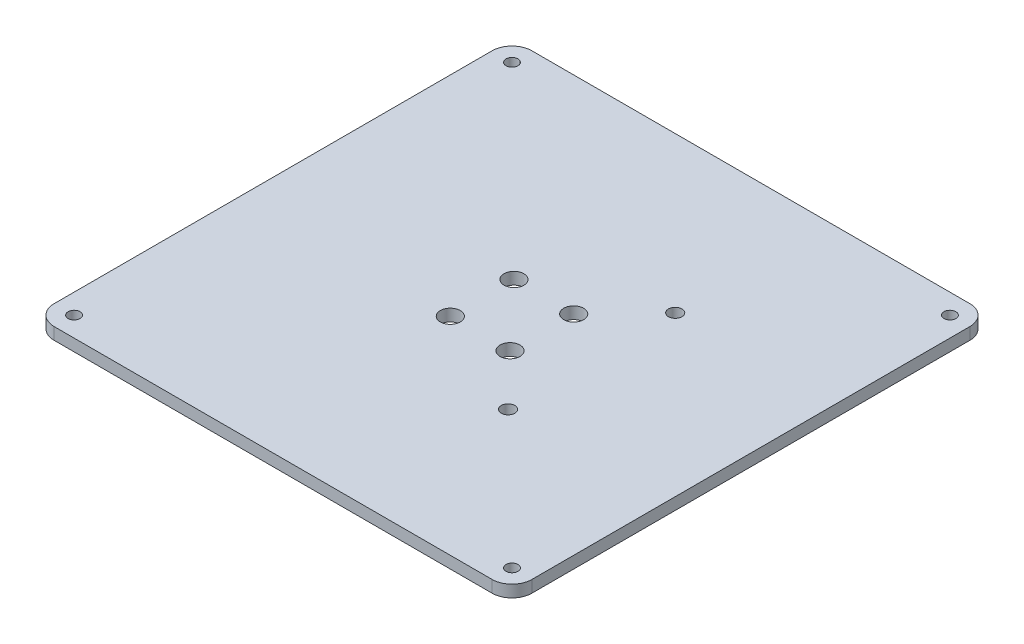
SolidWorks part; units mm, degrees
ref_plane "Alzado" through (0, 0, 0) normal (0, 0, 1) x (1, 0, 0)
ref_plane "Planta" through (0, 0, 0) normal (0, 1, 0) x (1, 0, 0)
ref_plane "Vista lateral" through (0, 0, 0) normal (1, 0, 0) x (0, 0, -1)
sketch "Sketch1" plane through (0, 0, 0) normal (0, 1, 0) x (1, 0, 0)
  line L1 (-7.5, -8) -> (7.5, -8) construction
  line L2 (-7.5, -8) -> (-7.5, 8) construction
  line L3 (-7.5, 8) -> (7.5, 8) construction
  line L4 (7.5, -8) -> (7.5, 8) construction
  line L5 (-7.5, -8) -> (7.5, 8) construction
  line L6 (-7.5, 8) -> (7.5, -8) construction
  line L7 (-60, -60) -> (60, -60)
  line L8 (-60, -60) -> (-60, 60)
  line L9 (-60, 60) -> (60, 60)
  line L10 (60, -60) -> (60, 60)
  circle A0 centre (-7.5, -8) radius 2.5
  circle A1 centre (7.5, 8) radius 2.5
  circle A2 centre (7.5, -8) radius 2.5
  circle A3 centre (-7.5, 8) radius 2.5
  point P0 (0, 0)
  point P10 (0, 0)
  point P16 (-60, 0)
  point P17 (0, -60)
  dimension "D3" = 5
  dimension "D1" = 16
  dimension "D2" = 15
  dimension "D4" = 120
  dimension "D5" = 120
extrude "Boss-Extrude1" add sketch "Sketch1" along normal blind 3
fillet "Fillet1" radius 5 4 edges at (-60, 1.5, -60) (60, 1.5, -60) (60, 1.5, 60) (-60, 1.5, 60)
sketch "Sketch2" plane through (0, 3, 0) normal (0, 1, 0) x (1, 0, 0)
  line L0 (-55, 55) -> (-55, 60) construction
  line L1 (-55, 55) -> (-60, 55) construction
  circle A0 centre (-55, 55) radius 1.5
  dimension "D1" = 3
extrude "Cut-Extrude1" cut sketch "Sketch2" against normal through all
mirror "Mirror3" about plane through (0, 0, 0) normal (0, 0, 1) of "Cut-Extrude1" second plane through (0, 0, 0) second plane normal (1, 0, 0)
sketch "Sketch3" plane through (0, 3, 0) normal (0, 1, 0) x (1, 0, 0)
  line L0 (20, 21) -> (20, -21) construction
  circle A2 centre (20, 21) radius 1.7
  circle A3 centre (20, -21) radius 1.7
  point P4 (20, 0)
  dimension "D2" = 42
  dimension "D1" = 3.4
  dimension "D3" = 20
extrude "Cut-Extrude2" cut sketch "Sketch3" against normal through all
